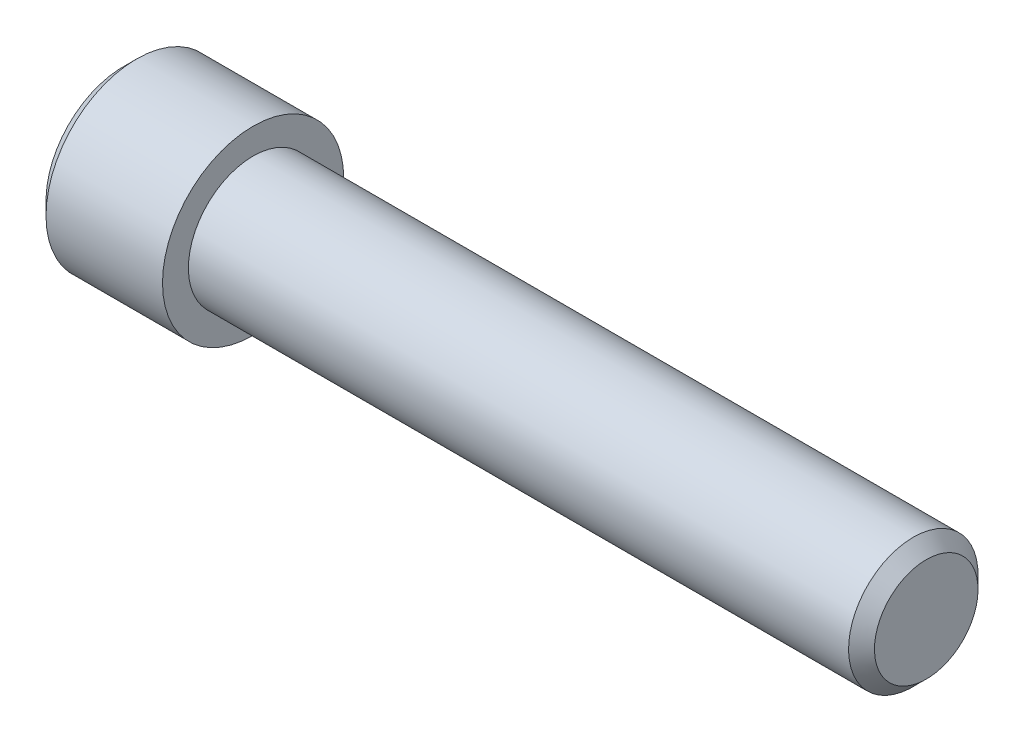
SolidWorks part; units mm, degrees
material "AISI 4130 Steel, annealed at 865C"
ref_plane "Front Plane" through (0, 0, 0) normal (0, 0, 1) x (1, 0, 0)
ref_plane "Top Plane" through (0, 0, 0) normal (0, 1, 0) x (1, 0, 0)
ref_plane "Right Plane" through (0, 0, 0) normal (1, 0, 0) x (0, 0, -1)
sketch "Sketch1" plane through (0, 0, 0) normal (0, 0, 1) x (1, 0, 0)
  line L0 (0, 0) -> (0, 3.5)
  line L1 (0, 3.5) -> (5, 3.5)
  line L2 (5, 3.5) -> (5, 2.5)
  line L3 (5, 2.5) -> (31, 2.5)
  line L4 (31, 2.5) -> (31, 0)
  line L5 (31, 0) -> (0, 0)
  dimension "D1" = 26
  dimension "D2" = 2.5
  dimension "D3" = 3.5
  dimension "D4" = 5
revolve "Revolve1" add sketch "Sketch1" angle 360 about L5
cosmetic thread "Cosmetic Thread1" parameters "D1"=5, "D2"=4.11
sketch "Sketch2" plane through (0, 0, 0) normal (-1, 0, 0) x (0, 0, 1)
  line L1 (0, 2.5) -> (-2.1651, 1.25)
  line L2 (-2.1651, 1.25) -> (-2.1651, -1.25)
  line L3 (-2.1651, -1.25) -> (0, -2.5)
  line L4 (0, -2.5) -> (2.1651, -1.25)
  line L5 (2.1651, -1.25) -> (2.1651, 1.25)
  line L6 (2.1651, 1.25) -> (0, 2.5)
  circle A0 centre (0, 0) radius 2.1651 construction
  dimension "D1" = 2.5
extrude "Cut-Extrude1" cut sketch "Sketch2" against normal blind 3
chamfer "Chamfer1" distance 0.5 angle 45 2 edges at (31, 2.5, 0) (0, 3.5, 0)
